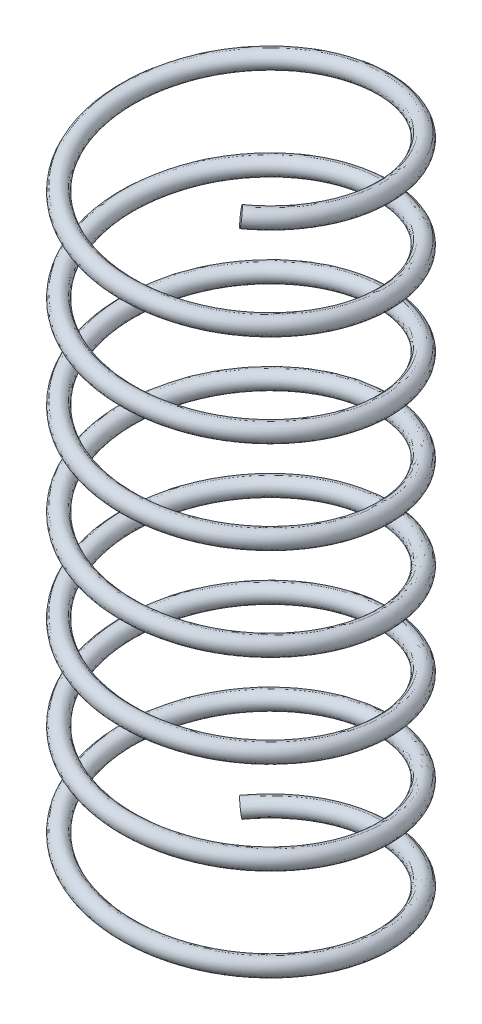
SolidWorks part; units mm, degrees
ref_plane "Front Plane" through (0, 0, 0) normal (0, 0, 1) x (1, 0, 0)
ref_plane "Top Plane" through (0, 0, 0) normal (0, 1, 0) x (1, 0, 0)
ref_plane "Right Plane" through (0, 0, 0) normal (1, 0, 0) x (0, 0, -1)
sketch "Sketch1" plane through (0, 0, 0) normal (0, 1, 0) x (1, 0, 0)
  circle A0 centre (0, 0) radius 4.0005
  dimension "D1" = 8.001
curve "Helix/Spiral1" pitch 2.8702 height 21.5265 turns 7.5
ref_plane "Plane1" through (2.8288, 21.5265, 2.8288) normal (-0.7025, 0.1135, 0.7025) x (0.6936, -0.112, 0.7116)
sketch "Sketch2" plane through (2.8288, 21.5265, 2.8288) normal (-0.7025, 0.1135, 0.7025) x (0.6936, -0.112, 0.7116)
  circle A0 centre (0, 0) radius 0.2667
  dimension "D1" = 0.5334
sweep "Sweep1" add profiles "Sketch2" path "Helix/Spiral1"
